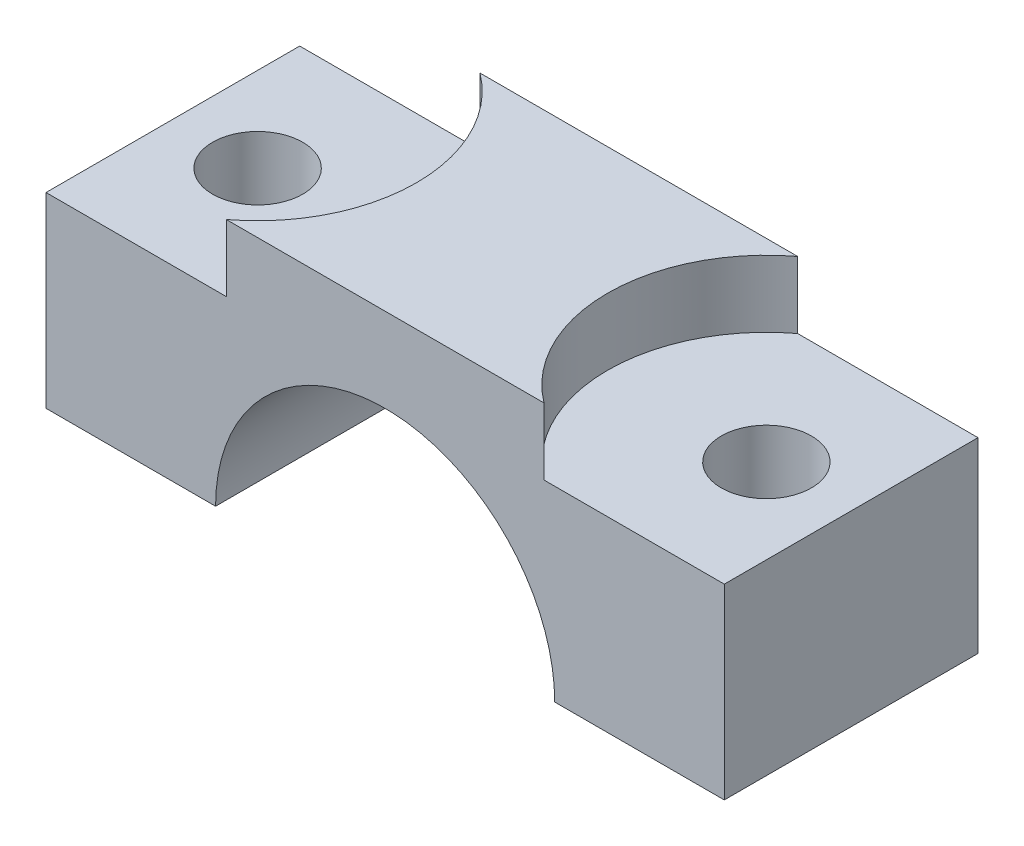
SolidWorks part; units mm, degrees
ref_plane "Front Plane" through (0, 0, 0) normal (0, 0, 1) x (1, 0, 0)
ref_plane "Top Plane" through (0, 0, 0) normal (0, 1, 0) x (1, 0, 0)
ref_plane "Right Plane" through (0, 0, 0) normal (1, 0, 0) x (0, 0, -1)
sketch "Sketch1" plane through (0, 0, 0) normal (0, 0, 1) x (1, 0, 0)
  line L0 (12.7, 0) -> (25.4, 0)
  line L1 (25.4, 0) -> (25.4, 19)
  line L2 (25.4, 19) -> (-25.4, 19)
  line L3 (-25.4, 19) -> (-25.4, 0)
  line L4 (-25.4, 0) -> (-12.7, 0)
  arc A0 (12.7, 0) -> (-12.7, 0) centre (0, 0) ccw
  dimension "D1" = 25.4
  dimension "D2" = 19
  dimension "D3" = 50.8
  dimension "D4" = 19
  dimension "D5" = 25.4
extrude "Boss-Extrude1" add sketch "Sketch1" along normal blind 19
sketch "Sketch2" plane through (0, 0, 0) normal (0, 1, 0) x (1, 0, 0)
  line L0 (-25.4, -9.5) -> (-12.7, -9.5)
  line L3 (-25.4, -19) -> (-25.4, 0) construction
  line L4 (-12.7, -19) -> (-12.7, 0) construction
  line L5 (12.7, -9.5) -> (25.4, -9.5)
  line L7 (25.4, -9.5) -> (12.7, -9.5)
  line L8 (12.7, -19) -> (12.7, 0) construction
  point P6 (-19.05, -9.5)
  point P11 (19.05, -9.5)
  dimension "D1" = 12.7
  dimension "D2" = 38.1
  dimension "D3" = 12.7
hole_wizard "Hole1" positions "Sketch3" profile "Sketch4" legacy
sketch "Sketch3" plane through (0, 19, 0) normal (0, 1, 0) x (1, 0, 0)
  point P0 (19.05, -9.5)
  point P3 (-19.05, -9.5)
sketch "Sketch4" plane through (19.05, 19, 9.5) normal (1, 0, 0) x (0, 0, 1)
  line L0 (0, 0) -> (0, 100)
  line L1 (0, 100) -> (3.375, 100)
  line L2 (3.375, 100) -> (3.375, 5)
  line L3 (3.375, 5) -> (11.8925, 5)
  line L4 (11.8925, 5) -> (11.8925, 0)
  line L5 (11.8925, 0) -> (0, 0)
  line L6 (0, 110) -> (0, -10) construction
  dimension "Diameter" = 6.75
  dimension "Depth" = 100
  dimension "C-Bore Diameter" = 23.785
  dimension "C-Bore Depth" = 5
